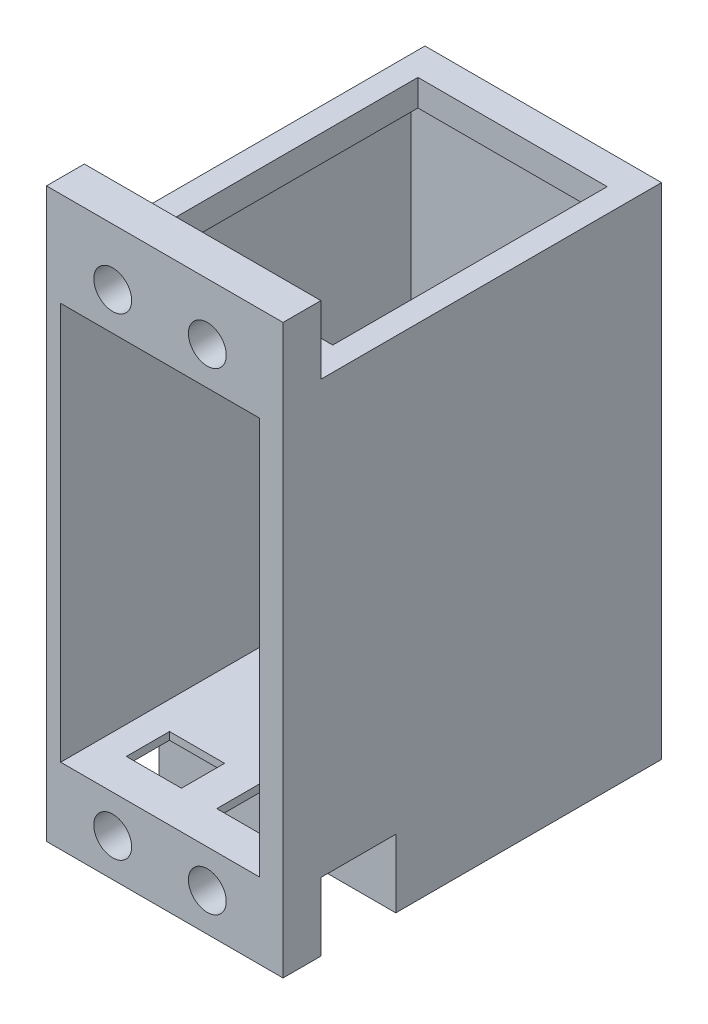
SolidWorks part; units mm, degrees
ref_plane "Front Plane" through (0, 0, 0) normal (0, 0, 1) x (1, 0, 0)
ref_plane "Top Plane" through (0, 0, 0) normal (0, 1, 0) x (1, 0, 0)
ref_plane "Right Plane" through (0, 0, 0) normal (1, 0, 0) x (0, 0, -1)
sketch "Sketch2" plane through (0, 0, 0) normal (0, 1, 0) x (1, 0, 0)
  line L1 (-12.5, -20) -> (12.5, -20)
  line L2 (-12.5, -20) -> (-12.5, 20)
  line L3 (-12.5, 20) -> (12.5, 20)
  line L4 (12.5, -20) -> (12.5, 20)
  line L5 (-12.5, -20) -> (12.5, 20) construction
  line L6 (-12.5, 20) -> (12.5, -20) construction
  point P0 (0, 0)
  dimension "D1" = 25
  dimension "D2" = 40
extrude "Boss-Extrude3" add sketch "Sketch2" along normal blind 60
sketch "Sketch13" plane through (0, 0, 20) normal (0, 0, 1) x (1, 0, 0)
  line L6 (10, 8) -> (-11, 8)
  line L7 (10, 8) -> (10, 50)
  line L8 (10, 50) -> (-11, 50)
  line L9 (-11, 8) -> (-11, 50)
  line L10 (10, 8) -> (-11, 50) construction
  line L11 (10, 50) -> (-11, 8) construction
  point P11 (-0.5, 29)
  dimension "D1" = 21
  dimension "D2" = 42
extrude "Cut-Extrude5" cut sketch "Sketch13" against normal blind 37
sketch "Sketch15" plane through (0, 0, 0) normal (0, -1, 0) x (1, 0, 0)
  line L0 (-12.5, 20) -> (-12.5, 16)
  line L1 (-12.5, -20) -> (-12.5, 20) construction
  line L2 (12.5, 20) -> (12.5, -20) construction
  line L3 (-12.5, 16) -> (12.5, 16)
  line L4 (-12.5, 16) -> (-12.5, 8.0844)
  line L5 (-12.5, 8.0844) -> (12.5, 8.0844)
  line L6 (12.5, 16) -> (12.5, 8.0844)
  dimension "D1" = 4
extrude "Cut-Extrude7" cut sketch "Sketch15" against normal blind 7.2 contours L3 L5 L1
sketch "Sketch16" plane through (0, 0, 0) normal (0, -1, 0) x (1, 0, 0)
  circle A0 centre (0, -11.2402) radius 1.5
extrude "Cut-Extrude8" cut sketch "Sketch16" against normal blind 8
sketch "Sketch17" plane through (0, 60, 0) normal (0, 1, 0) x (1, 0, 0)
  line L0 (12.5, -20) -> (12.5, -16)
  line L1 (12.5, -20) -> (12.5, 20) construction
  line L2 (-12.5, 20) -> (-12.5, -20) construction
  line L3 (12.5, -16) -> (-12.5, -16)
  line L4 (12.5, -16) -> (12.5, 20)
  line L5 (12.5, 20) -> (-12.5, 20)
  line L6 (-12.5, -16) -> (-12.5, 20)
  line M2 (12.5, -20) -> (12.5, 20)
  line M3 (12.5, 20) -> (-12.5, 20)
  line M4 (-12.5, 20) -> (-12.5, -20)
  dimension "D1" = 4
extrude "Cut-Extrude9" cut sketch "Sketch17" against normal blind 7.2 contours L3 M2 M3 M4
sketch "Sketch19" plane through (0, 52.8, 0) normal (0, 1, 0) x (1, 0, 0)
  line L0 (-12.5, -12.2443) -> (-10, -12.2443)
  line L1 (-12.5, 20) -> (-12.5, -16) construction
  line L2 (12.5, -12.2443) -> (10, -12.2443)
  line L3 (12.5, -16) -> (12.5, 20) construction
  line L4 (-10, -12.2443) -> (-10, 16.7557)
  line L5 (-10, 16.7557) -> (10, 16.7557)
  line L6 (10, 16.7557) -> (10, -12.2443)
  line L7 (-10, -12.2443) -> (10, -12.2443)
  dimension "D1" = 20
  dimension "D2" = 29
extrude "Cut-Extrude10" cut sketch "Sketch19" against normal blind 4 contours L4 L7 L6 L5
sketch "Sketch23" plane through (0, 0, 20) normal (0, 0, 1) x (1, 0, 0)
  circle A0 centre (-5.5, 54) radius 2
  circle A1 centre (4.5, 54) radius 2
  circle A2 centre (-5.5, 4) radius 2
  circle A3 centre (4.5, 4) radius 2
  point P12 (-0.5, 29)
  dimension "D1" = 10
  dimension "D2" = 50
extrude "Cut-Extrude12" cut sketch "Sketch23" against normal blind 10
sketch "Sketch24" plane through (0, 7.2, 0) normal (0, -1, 0) x (1, 0, 0)
  line L0 (-12.5, 16) -> (12.5, 16) construction
  line L1 (-8.0587, 16) -> (-2.2369, 16)
  line L2 (-8.0587, 16) -> (-8.0587, 11.4399)
  line L3 (-8.0587, 11.4399) -> (-2.2369, 11.4399)
  line L4 (-2.2369, 16) -> (-2.2369, 11.4399)
  line L6 (1.4952, 16) -> (7.5433, 16)
  line L7 (1.4952, 16) -> (1.4952, 11.4399)
  line L8 (1.4952, 11.4399) -> (7.5433, 11.4399)
  line L9 (7.5433, 16) -> (7.5433, 11.4399)
extrude "Cut-Extrude14" cut sketch "Sketch24" against normal blind 1
sketch "Sketch25" plane through (0, 52.8, 0) normal (0, 1, 0) x (1, 0, 0)
  line L0 (12.5, -16) -> (-12.5, -16) construction
  line L1 (-7.1, -12.2443) -> (-3.9, -12.2443)
  line L2 (-7.1, -12.2443) -> (-7.1, -16)
  line L3 (-7.1, -16) -> (-3.9, -16)
  line L4 (-3.9, -12.2443) -> (-3.9, -16)
  line L5 (-3.9, -16) -> (-3.9, -12.2443) construction
  line L7 (2.9, -12.2443) -> (6.1, -12.2443)
  line L8 (2.9, -12.2443) -> (2.9, -16)
  line L9 (2.9, -16) -> (6.1, -16)
  line L10 (6.1, -12.2443) -> (6.1, -16)
extrude "Cut-Extrude15" cut sketch "Sketch25" against normal blind 1
sketch "Sketch28" plane through (0, 0, -20) normal (0, 0, -1) x (-1, 0, 0)
  line L0 (0, 52.8) -> (0, 40)
  line L1 (-12.5, 52.8) -> (12.5, 52.8) construction
  circle A0 centre (0, 40) radius 1.5
  dimension "D1" = 12.8
extrude "Boss-Extrude4" add sketch "Sketch28" along normal blind 4
sketch "Sketch29" plane through (0, 0, 0) normal (0, -1, 0) x (1, 0, 0)
  circle A0 centre (0, -4.2402) radius 1
  circle A2 centre (-7, -11.2402) radius 1
  circle A3 centre (7, -11.2402) radius 1
extrude "Cut-Extrude16" cut sketch "Sketch29" against normal blind 10
